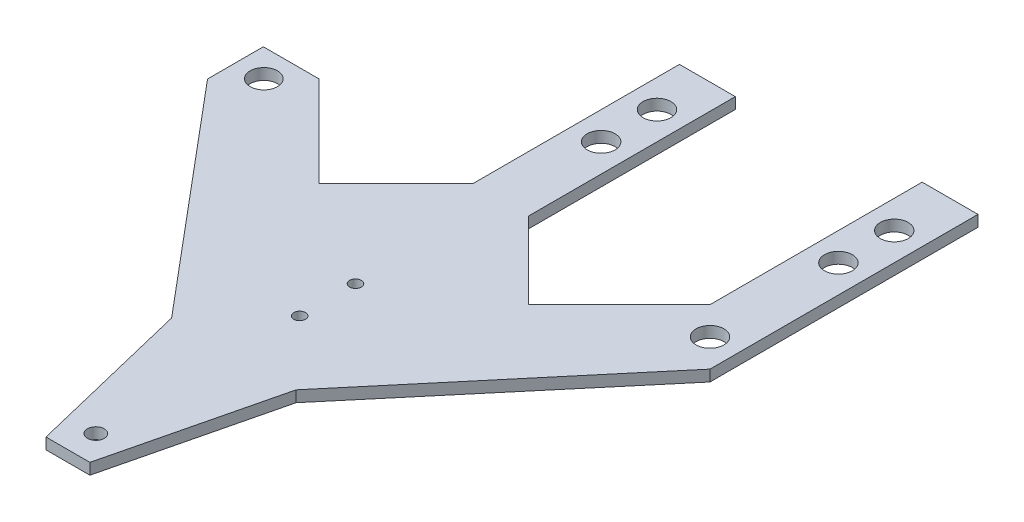
SolidWorks part; units mm, degrees
ref_plane "Front Plane" through (0, 0, 0) normal (0, 0, 1) x (1, 0, 0)
ref_plane "Top Plane" through (0, 0, 0) normal (0, 1, 0) x (1, 0, 0)
ref_plane "Right Plane" through (0, 0, 0) normal (1, 0, 0) x (0, 0, -1)
sketch "Sketch1" plane through (0, 0, 0) normal (0, 1, 0) x (1, 0, 0)
  line L0 (45, 45) -> (45, 35)
  line L2 (3.9309, -35) -> (-3.9309, -35)
  line L4 (35, 45) -> (18.75, 28.75)
  line L5 (45, 35) -> (11.1499, -5.2793)
  line L6 (11.1499, -5.2793) -> (3.9309, -35)
  line L7 (35, 45) -> (35, 83)
  line L8 (35, 83) -> (45, 83)
  line L9 (45, 83) -> (45, 45)
  line L10 (5, 42.5) -> (18.75, 28.75)
  line L12 (-5.004, 42.5) -> (-5.004, 79.5315)
  line L13 (-5.004, 79.5315) -> (5, 79.5315)
  line L14 (5, 79.5315) -> (5, 42.5)
  line L15 (-11.1499, -5.2793) -> (-3.9309, -35)
  line L16 (-45, 35) -> (-11.1499, -5.2793)
  line L17 (-45, 45) -> (-45, 35)
  line L18 (-45, 45) -> (-35, 45)
  line L19 (-35, 45) -> (-18.75, 28.75)
  line L20 (-18.75, 28.75) -> (-5.004, 42.5)
  circle A0 centre (-40, 40.0812) radius 2.4528
  circle A1 centre (40, 40) radius 2.5
  circle A2 centre (40, 63) radius 2.5
  circle A3 centre (40, 73) radius 2.5
  circle A4 centre (-0.004, 60.5) radius 2.5
  circle A5 centre (0, 70.5) radius 2.5
  circle A6 centre (0, 6.5) radius 1.05
  circle A7 centre (0, 16.5) radius 1.05
  circle A8 centre (0, -30) radius 1.5
  point P35 (0, -35)
  dimension "D1" = 80
  dimension "D11" = 5
  dimension "D12" = 5
  dimension "D14" = 5
  dimension "D17" = 5
  dimension "D19" = 5
  dimension "D23" = 2.1
  dimension "D24" = 2.1
  dimension "D26" = 3
  dimension "D2" = 40
  dimension "D3" = 5
  dimension "D5" = 6.5
  dimension "D6" = 16.5
  dimension "D7" = 40
  dimension "D8" = 35
  dimension "D13" = 10
  dimension "D18" = 10
  dimension "D20" = 5
  dimension "D21" = 5
  dimension "D22" = 40
  dimension "D25" = 30
  dimension "D27" = 5
extrude "Boss-Extrude1" add sketch "Sketch1" along normal blind 2
